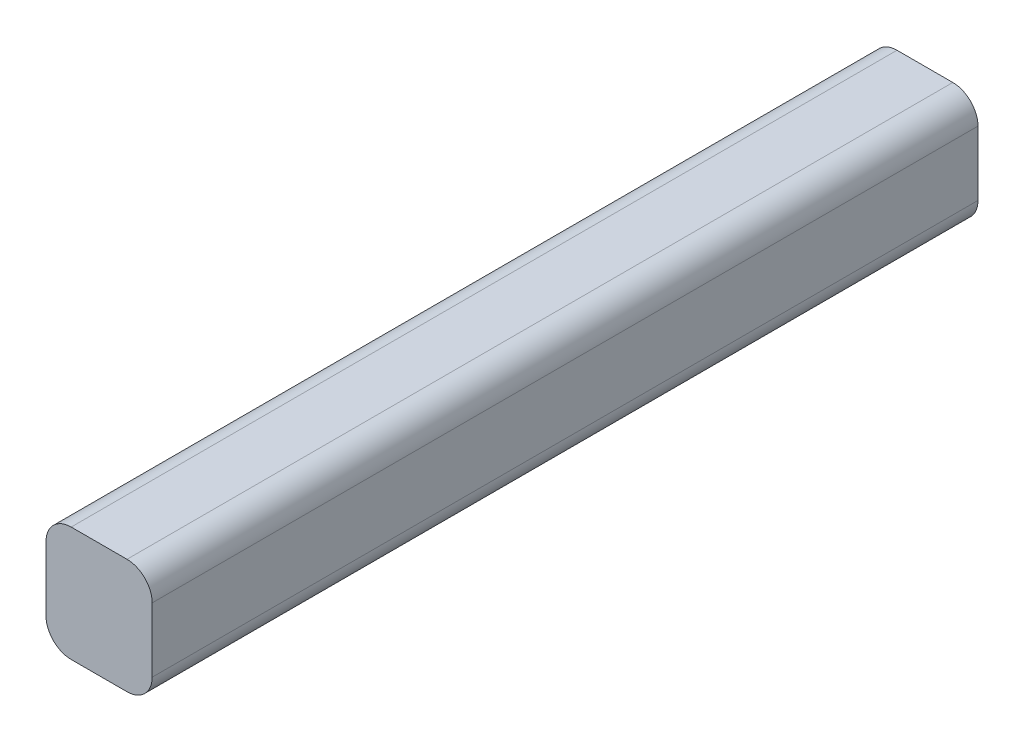
SolidWorks part; units mm, degrees
ref_plane "Front Plane" through (0, 0, 0) normal (0, 0, 1) x (1, 0, 0)
ref_plane "Top Plane" through (0, 0, 0) normal (0, 1, 0) x (1, 0, 0)
ref_plane "Right Plane" through (0, 0, 0) normal (1, 0, 0) x (0, 0, -1)
sketch "Sketch1" plane through (0, 0, 0) normal (0, 0, 1) x (1, 0, 0)
  line L1 (22.78, 22.78) -> (22.78, -22.79)
  line L2 (22.78, -22.79) -> (-19.39, -22.79)
  line L3 (-19.39, -22.79) -> (-19.39, 22.78)
  line L5 (-19.39, 22.78) -> (22.78, 22.78)
  dimension "D1" = 45.57
  dimension "D2" = 42.17
extrude "Boss-Extrude1" add sketch "Sketch1" along normal blind 328
fillet "Fillet1" radius 10 4 edges at (-19.39, -22.79, 164) (-19.39, 22.78, 164) (22.78, 22.78, 164) (22.78, -22.79, 164)
